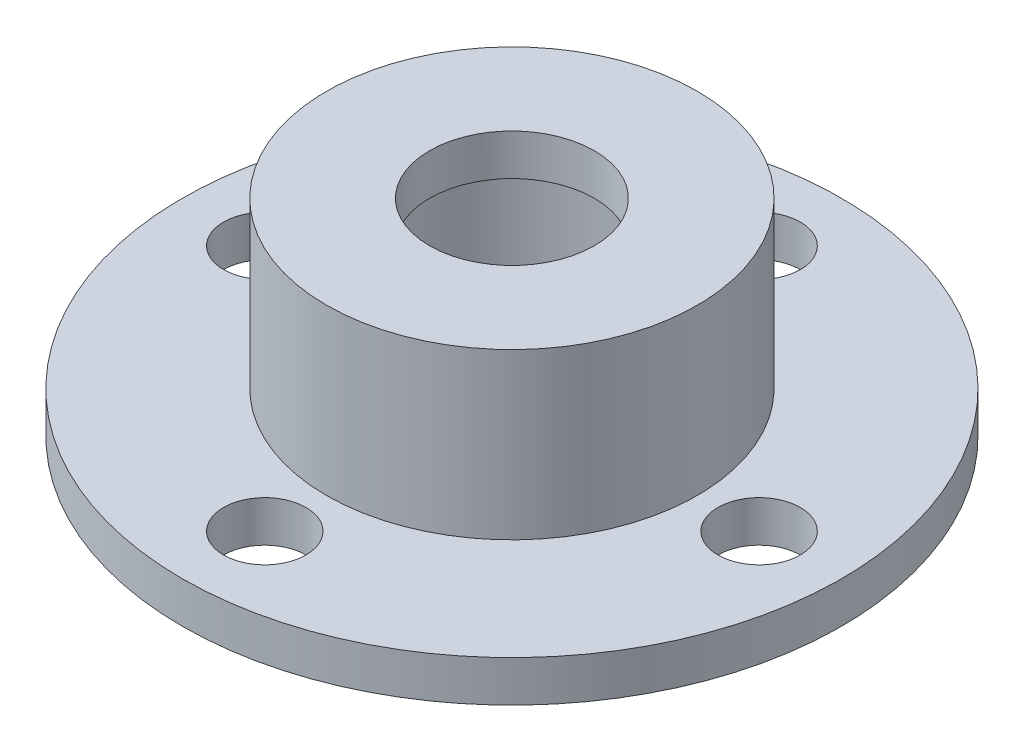
SolidWorks part; units mm, degrees
ref_plane "Front Plane" through (0, 0, 0) normal (0, 0, 1) x (1, 0, 0)
ref_plane "Top Plane" through (0, 0, 0) normal (0, 1, 0) x (1, 0, 0)
ref_plane "Right Plane" through (0, 0, 0) normal (1, 0, 0) x (0, 0, -1)
sketch "Sketch1" plane through (0, 0, 0) normal (0, 1, 0) x (1, 0, 0)
  line L0 (0, -203.2) -> (0, 203.2)
  line L1 (203.2, 0) -> (-203.2, 0)
  circle A0 centre (0, 0) radius 203.2
  circle A1 centre (0, 0) radius 50.8
  circle A2 centre (0, 0) radius 152.4
  circle A3 centre (0, 152.4) radius 25.4
  circle A4 centre (152.4, 0) radius 25.4
  circle A5 centre (0, -152.4) radius 25.4
  circle A6 centre (-152.4, 0) radius 25.4
  dimension "D1" = 406.4
  dimension "D2" = 304.8
  dimension "D3" = 101.6
  dimension "D4" = 50.8
  dimension "D5" = 50.8
  dimension "D6" = 50.8
  dimension "D7" = 50.8
extrude "Boss-Extrude1" add sketch "Sketch1" along normal blind 25.4 contours A6 L1 A0 L0 A5 A2 | A6 A2 A5 L0 A1 L1 | A6 A2 A3 L0 A0 L1 | A6 L1 A1 L0 A3 A2 | A5 A2 A4 L1 A1 L0 | A5 L0 A0 L1 A4 A2 | A4 A2 A3 L0 A1 L1 | A4 L1 A0 L0 A3 A2
sketch "Sketch2" plane through (0, 25.4, 0) normal (0, 1, 0) x (1, 0, 0)
  circle A0 centre (0, 0) radius 114.3
  circle A1 centre (0, 0) radius 50.8
  dimension "D1" = 228.6
extrude "Boss-Extrude3" add sketch "Sketch2" along normal blind 101.6
sketch "Sketch3" plane through (0, 0, 0) normal (0, -1, 0) x (1, 0, 0)
  circle A0 centre (0, 0) radius 76.2
  dimension "D1" = 152.4
extrude "Cut-Extrude1" cut sketch "Sketch3" against normal blind 101.6 contours A0
